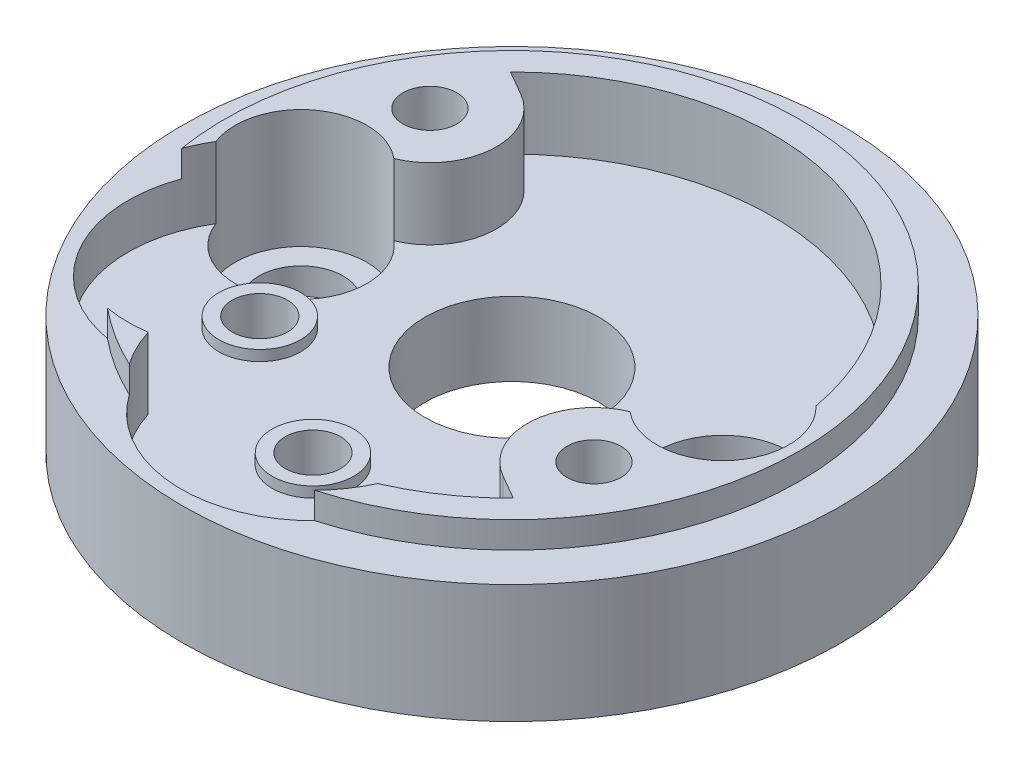
SolidWorks part; units mm, degrees
material "PET"
ref_plane "Front Plane" through (0, 0, 0) normal (0, 0, 1) x (1, 0, 0)
ref_plane "Top Plane" through (0, 0, 0) normal (0, 1, 0) x (1, 0, 0)
ref_plane "Right Plane" through (0, 0, 0) normal (1, 0, 0) x (0, 0, -1)
sketch "Sketch1" plane through (0, 0, 0) normal (0, 1, 0) x (1, 0, 0)
  circle A0 centre (0, 0) radius 12.5
  dimension "D1" = 25
extrude "Boss-Extrude1" add sketch "Sketch1" along normal blind 5.5
sketch "Sketch2" plane through (0, 5.5, 0) normal (0, 1, 0) x (1, 0, 0)
  circle A0 centre (0, 0) radius 10.9
  dimension "D1" = 21.8
extrude "Cut-Extrude1" cut sketch "Sketch2" against normal blind 1 flip side to cut
sketch "Sketch3" plane through (0, 5.5, 0) normal (0, 1, 0) x (1, 0, 0)
  circle A0 centre (0, 0) radius 9.9
  circle A1 centre (0, 0) radius 10.9 construction
  dimension "D1" = 1
extrude "Cut-Extrude2" cut sketch "Sketch3" against normal offset from surface (2.7 mm away) 2.8 up to face at (0, 0, 12.5)
sketch "Sketch4" plane through (0, 0, 0) normal (0, -1, 0) x (1, 0, 0)
  line L0 (-8, 0) -> (8, 0) construction
  circle A0 centre (0, 0) radius 3.3
  circle A1 centre (8, 0) radius 1.6
  circle A2 centre (-8, 0) radius 1.6
  point P7 (-6.4, 0)
  point P8 (-9.6, 0)
  point P9 (9.6, 0)
  point P10 (6.4, 0)
  dimension "D1" = 6.6
  dimension "D4" = 3.2
  dimension "D5" = 16
extrude "Cut-Extrude3" cut sketch "Sketch4" against normal through all
sketch "Sketch5" plane through (0, 0, 0) normal (0, -1, 0) x (1, 0, 0)
  circle A0 centre (-8, 0) radius 2.5
  circle A1 centre (8, 0) radius 2.5
  dimension "D1" = 5
extrude "Cut-Extrude4" cut sketch "Sketch5" against normal through all from offset 1 offset against normal yes
sketch "Sketch6" plane through (0, 0, 0) normal (0, -1, 0) x (1, 0, 0)
  line L0 (7.3612, 4.25) -> (-7.3612, -4.25) construction
  line L1 (0, 0) -> (9.2252, 0) construction
  circle A0 centre (-7.3612, -4.25) radius 1.025
  circle A1 centre (7.3612, 4.25) radius 1.025
  dimension "D1" = 17
  dimension "D2" = 2.05
  dimension "D3" = 30
extrude "Cut-Extrude5" cut sketch "Sketch6" against normal through all
sketch "Sketch7" plane through (0, 2.8, 0) normal (0, 1, 0) x (1, 0, 0)
  line L0 (-7.0276, 6.973) -> (-6.0987, 6.4367)
  line L1 (-9.5526, 2.5996) -> (-9.0106, 2.2866)
  line L2 (0, 0) -> (-8.5737, 4.95) construction
  circle A1 centre (-7.3612, 4.25) radius 1.025 construction
  circle A3 centre (-7.3612, 4.25) radius 1.025
  arc A4 (-9.5526, 2.5996) -> (-7.0276, 6.973) centre (0, 0) cw
  arc A5 (9.735, 1.7999) -> (-9.735, 1.7999) centre (0, 0) ccw construction
  arc A6 (9.735, 1.7999) -> (-9.735, 1.7999) centre (0, 0) ccw construction
  arc A7 (-6.0987, 6.4367) -> (-6.3953, 1.917) centre (-7.3612, 4.25) cw
  circle A8 centre (-8, 0) radius 2.5 construction
  arc A9 (-6.3953, 1.917) -> (-9.0106, 2.2866) centre (-8, 0) ccw
  dimension "D1" = 1.5
extrude "Boss-Extrude2" add sketch "Sketch7" along normal up to surface (2.7 mm away) up to face at (0, 5.5, 0)
sketch "Sketch8" plane through (0, 2.8, 0) normal (0, 1, 0) x (1, 0, 0)
  line L1 (-9.0106, 2.2866) -> (-9.5526, 2.5996)
  line L2 (-9.0106, 2.2866) -> (-9.5526, 2.5996)
  arc A2 (-9.0106, 2.2866) -> (-9.735, 1.7999) centre (-8, 0) ccw
  arc A3 (-9.5526, 2.5996) -> (-9.735, 1.7999) centre (0, 0) ccw
  arc A4 (-9.0106, 2.2866) -> (-9.735, 1.7999) centre (-8, 0) ccw
  arc A5 (-9.5526, 2.5996) -> (-9.735, 1.7999) centre (0, 0) ccw
  dimension "D1" = 0
extrude "Boss-Extrude3" add sketch "Sketch8" along normal up to surface (2.7 mm away) up to face at (-3.8966, 5.5, -1.941)
pattern_circular "CirPattern1" count 2 over 360 about axis through (0, 0, 0) along (0, 1, 0) of "Boss-Extrude2", "Boss-Extrude3"
sketch "Sketch9" plane through (0, 2.8, 0) normal (0, 1, 0) x (1, 0, 0)
  line L0 (-0.5702, -6.9767) -> (0, 0) construction
  line L1 (-6.0622, -3.5) -> (0, 0) construction
  line L2 (-6.0622, -3.5) -> (-0.5702, -6.9767) construction
  line L3 (0, 0) -> (-2.6836, 0) construction
  circle A0 centre (-6.0622, -3.5) radius 1.05
  circle A1 centre (-0.5702, -6.9767) radius 1.05
  dimension "D1" = 2.1
  dimension "D2" = 7
  dimension "D3" = 7
  dimension "D4" = 6.5
  dimension "D5" = 30
extrude "Cut-Extrude6" cut sketch "Sketch9" against normal through all
sketch "Sketch10" plane through (0, 2.8, 0) normal (0, 1, 0) x (1, 0, 0)
  circle A0 centre (-0.5702, -6.9767) radius 1.05 construction
  circle A1 centre (-6.0622, -3.5) radius 1.05 construction
  circle A2 centre (-0.5702, -6.9767) radius 1.05
  circle A3 centre (-6.0622, -3.5) radius 1.05
  circle A4 centre (-6.0622, -3.5) radius 1.55
  circle A5 centre (-0.5702, -6.9767) radius 1.55
  dimension "D1" = 0.5
extrude "Boss-Extrude4" add sketch "Sketch10" along normal blind 0.4
sketch "Sketch11" plane through (0, 2.8, 0) normal (0, 1, 0) x (1, 0, 0)
  arc A0 (-1.2838, -2.0279) -> (-5.3485, -8.4488) centre (-6.0622, -3.5) ccw
  arc A1 (-5.3485, -8.4488) -> (-1.2838, -2.0279) centre (-0.5702, -6.9767) ccw
  circle A2 centre (-6.0622, -3.5) radius 1.05 construction
  circle A4 centre (-6.0622, -3.5) radius 1.55 construction
  circle A5 centre (-6.0622, -3.5) radius 1.55
  circle A6 centre (-0.5702, -6.9767) radius 1.55 construction
  circle A7 centre (-0.5702, -6.9767) radius 1.55
  dimension "D1" = 10
extrude "Cut-Extrude7" cut sketch "Sketch11" along normal through all
equation "\"mounting_diam\"= 16"
equation "\"D5@Sketch4\"=\"mounting_diam\""
